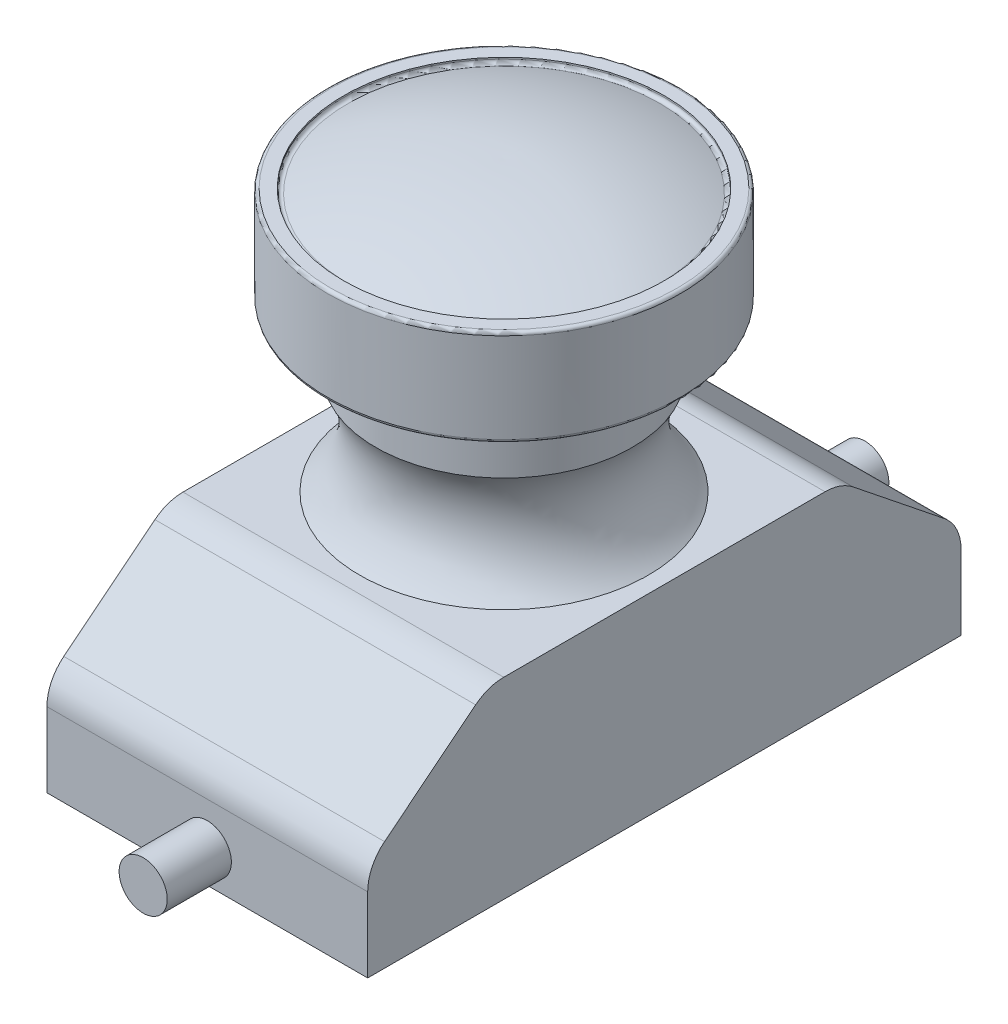
SolidWorks part; units mm, degrees
ref_plane "前视基准面" through (0, 0, 0) normal (0, 0, 1) x (1, 0, 0)
ref_plane "上视基准面" through (0, 0, 0) normal (0, 1, 0) x (1, 0, 0)
ref_plane "右视基准面" through (0, 0, 0) normal (1, 0, 0) x (0, 0, -1)
sketch "草图1" plane through (0, 0, 0) normal (1, 0, 0) x (0, 0, -1)
  line L0 (-9.25, 0) -> (9.25, 0)
  line L1 (-9.25, 0) -> (-9.25, 3)
  line L2 (-9.25, 3) -> (-5.5, 6)
  line L3 (-5.5, 6) -> (5.5, 6)
  line L4 (5.5, 6) -> (9.25, 3)
  line L5 (9.25, 3) -> (9.25, 0)
  line L6 (0, 0) -> (0, 12.455) construction
  point P3 (0, 0)
  dimension "D1" = 18.5
  dimension "D2" = 3
  dimension "D3" = 3
  dimension "D4" = 11
extrude "凸台-拉伸1" add sketch "草图1" along normal mid plane 10
sketch "草图2" plane through (0, 0, 0) normal (1, 0, 0) x (0, 0, -1)
  line L0 (0, 6) -> (0, 14)
  line L1 (5.5, 6) -> (-5.5, 6) construction
  line L2 (0, 14) -> (5, 14)
  line L3 (5, 14) -> (5, 14.2)
  line L4 (5, 14.2) -> (5.5, 14.2)
  line L5 (5.5, 14.2) -> (5.5, 11.2)
  line L6 (5.5, 11.2) -> (4, 11.2)
  line L7 (4, 11.2) -> (4, 9.2)
  line L8 (0, 6) -> (4.5, 6)
  arc A1 (4, 9.2) -> (4.5, 6) centre (6.1318, 7.894) ccw
  dimension "D8" = 2.5
  dimension "D1" = 4.5
  dimension "D2" = 0.2
  dimension "D3" = 5
  dimension "D4" = 0.5
  dimension "D5" = 3
  dimension "D6" = 8
  dimension "D7" = 2
  dimension "D9" = 1.5
revolve "旋转1" add sketch "草图2" angle 360 about L0
sketch "草图3" plane through (0, 0, 0) normal (1, 0, 0) x (0, 0, -1)
  line L0 (0, 14.2) -> (0, 15)
  line L1 (5.5, 14.2) -> (-5.5, 14.2) construction
  line L2 (0, 14.2) -> (0, 14)
  line L3 (0, 14) -> (-5, 14)
  arc A0 (0, 15) -> (-5, 14) centre (-0.2003, 3.0017) ccw
  dimension "D3" = 12
  dimension "D1" = 0.8
  dimension "D2" = 0.2
  dimension "D4" = 5
revolve "旋转2" add sketch "草图3" angle 360 about L0
fillet "圆角1" radius 0.1 2 edges at (0, 11.2, -5.5) (0, 14.2, -5.5)
fillet "圆角2" radius 0.1 1 edges at (0, 14, -5)
fillet "圆角3" radius 1.4 4 edges at (0, 3, 9.25) (0, 6, 5.5) (0, 3, -9.25) (0, 6, -5.5)
sketch "草图4" plane through (0, 0, -9.25) normal (0, 0, -1) x (-1, 0, 0)
  circle A0 centre (0, 1) radius 0.75
  dimension "D2" = 1.5
  dimension "D1" = 1
extrude "凸台-拉伸3" add sketch "草图4" along normal blind 2
mirror "镜向2" about plane through (0, 0, 0) normal (0, 0, 1) of "凸台-拉伸3"
